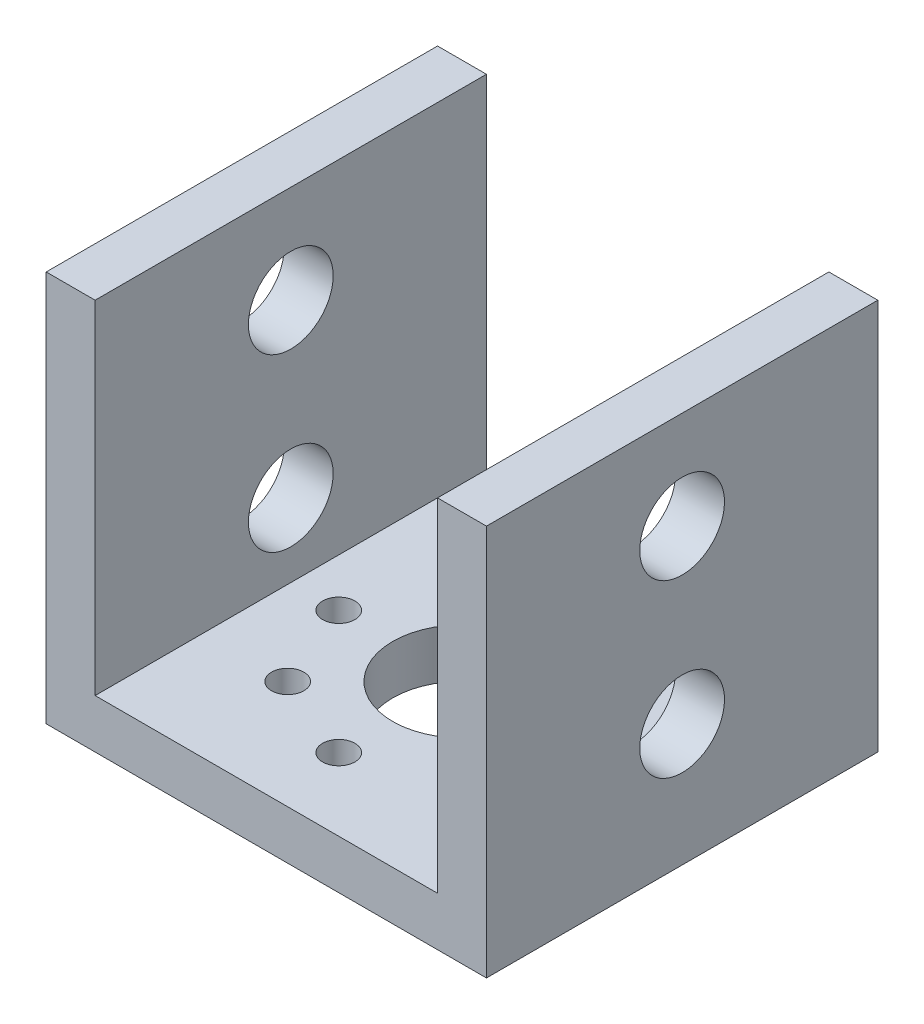
SolidWorks part; units mm, degrees
material "6063-T5"
ref_plane "Front Plane" through (0, 0, 0) normal (0, 0, 1) x (1, 0, 0)
ref_plane "Top Plane" through (0, 0, 0) normal (0, 1, 0) x (1, 0, 0)
ref_plane "Right Plane" through (0, 0, 0) normal (1, 0, 0) x (0, 0, -1)
sketch "Sketch1" plane through (0, 0, 0) normal (0, 0, 1) x (1, 0, 0)
  line L0 (-11.1125, 0) -> (11.1125, 0)
  line L1 (0, 0) -> (0, -3.175) construction
  line L2 (-14.2875, -3.175) -> (14.2875, -3.175)
  line L3 (14.2875, -3.175) -> (14.2875, 22.225)
  line L4 (-14.2875, -3.175) -> (-14.2875, 22.225)
  line L5 (-11.1125, 0) -> (-11.1125, 22.225)
  line L6 (-11.1125, 22.225) -> (-14.2875, 22.225)
  line L7 (11.1125, 0) -> (11.1125, 22.225)
  line L8 (11.1125, 22.225) -> (14.2875, 22.225)
  point P3 (0, 0)
  point P9 (0, -3.175)
  dimension "D1" = 22.225
  dimension "D2" = 3.175
  dimension "D3" = 28.575
  dimension "D4" = 25.4
extrude "Boss-Extrude1" add sketch "Sketch1" along normal blind 25.4
sketch "Sketch2" plane through (14.2875, 0, 0) normal (1, 0, 0) x (0, 0, -1)
  line L0 (-25.4, 22.225) -> (0, 22.225) construction
  line L1 (-25.4, -3.175) -> (-25.4, 22.225) construction
  line L3 (-25.4, -3.175) -> (0, -3.175) construction
  circle A0 centre (-12.7, 15.875) radius 2.75
  circle A1 centre (-12.7, 4.7625) radius 2.75
  point P6 (-12.7, 22.225)
  dimension "D1" = 5.5
  dimension "D4" = 7.9375
  dimension "D2" = 6.35
  dimension "D3" = 12.7
extrude "Cut-Extrude1" cut sketch "Sketch2" against normal through all
sketch "Sketch3" plane through (0, 0, 0) normal (0, 1, 0) x (1, 0, 0)
  line L0 (-11.1125, 0) -> (11.1125, -25.4) construction
  circle A0 centre (0, -12.7) radius 4.5
  point P6 (0, -4.7)
  point P10 (5.6569, -7.0431)
  point P11 (8, -12.7)
  point P12 (5.6569, -18.3569)
  point P13 (0, -20.7)
  point P14 (-5.6569, -18.3569)
  point P15 (-8, -12.7)
  point P16 (-5.6569, -7.0431)
  point P17 (0, -12.7)
  dimension "D1" = 9
  dimension "D2" = 8
  dimension "D3" = 8
extrude "Cut-Extrude2" cut sketch "Sketch3" against normal through all
hole_wizard "Ø2.0mm Dowel Hole1" positions "Sketch4" profile "Sketch5" hole size "Ø2.0" standard "ISO" end condition through all
sketch "Sketch4" plane through (0, 0, 0) normal (0, 1, 0) x (1, 0, 0)
  point P0 (0, -4.7)
  point P3 (5.6569, -7.0431)
  point P6 (8, -12.7)
  point P9 (5.6569, -18.3569)
  point P12 (0, -20.7)
  point P15 (-5.6569, -18.3569)
  point P18 (-8, -12.7)
  point P21 (-5.6569, -7.0431)
sketch "Sketch5" plane through (0, 0, 4.7) normal (1, 0, 0) x (0, 0, 1)
  line L0 (0, 0) -> (0, 3.175)
  line L1 (0, 3.175) -> (1.05, 3.175)
  line L2 (1.05, 3.175) -> (1.05, 0)
  line L5 (1.05, 0) -> (0, 0)
  line L11 (0, -6.35) -> (0, 107.95) construction
  dimension "Thru Hole Dia." = 2.1
  dimension "Thru Hole Depth" = 3.175
